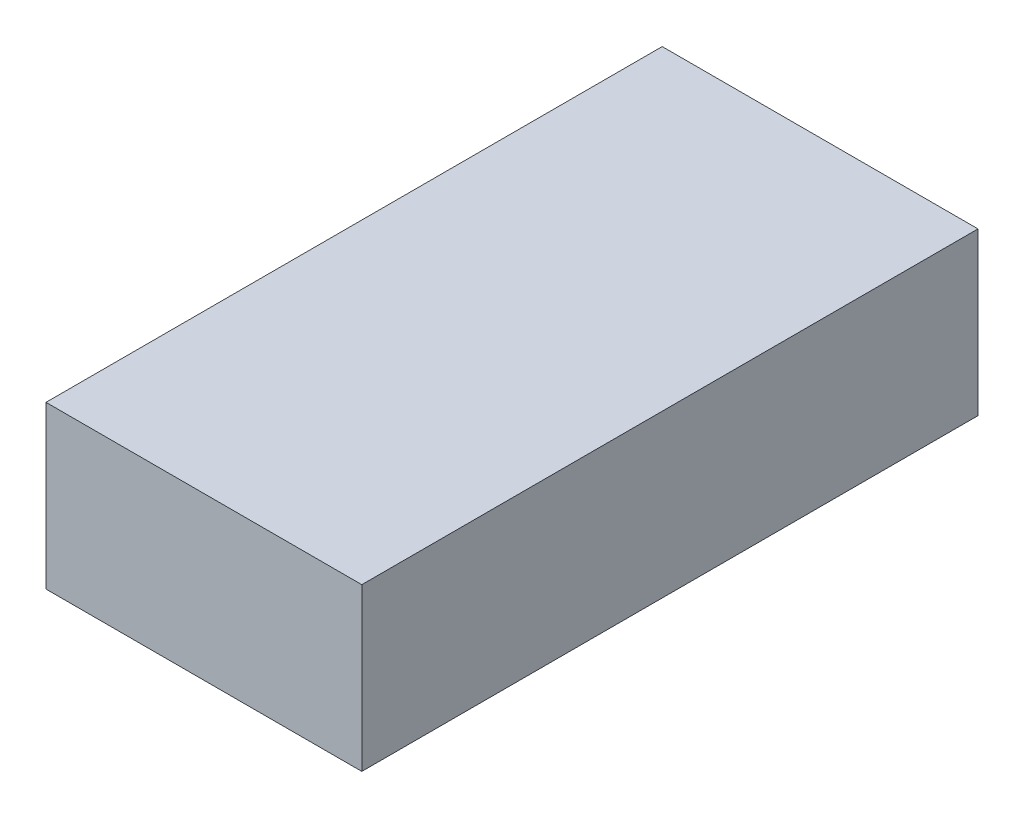
SolidWorks part; units mm, degrees
ref_plane "Front Plane" through (0, 0, 0) normal (0, 0, 1) x (1, 0, 0)
ref_plane "Top Plane" through (0, 0, 0) normal (0, 1, 0) x (1, 0, 0)
ref_plane "Right Plane" through (0, 0, 0) normal (1, 0, 0) x (0, 0, -1)
sketch "Sketch1" plane through (0, 0, 0) normal (0, 0, 1) x (1, 0, 0)
  line L1 (-20.5, 10.5) -> (20.5, 10.5)
  line L2 (-20.5, 10.5) -> (-20.5, -10.5)
  line L3 (-20.5, -10.5) -> (20.5, -10.5)
  line L4 (20.5, 10.5) -> (20.5, -10.5)
  line L5 (-20.5, 10.5) -> (20.5, -10.5) construction
  line L6 (-20.5, -10.5) -> (20.5, 10.5) construction
  point P0 (0, 0)
extrude "Boss-Extrude1" add sketch "Sketch1" along normal blind 80
